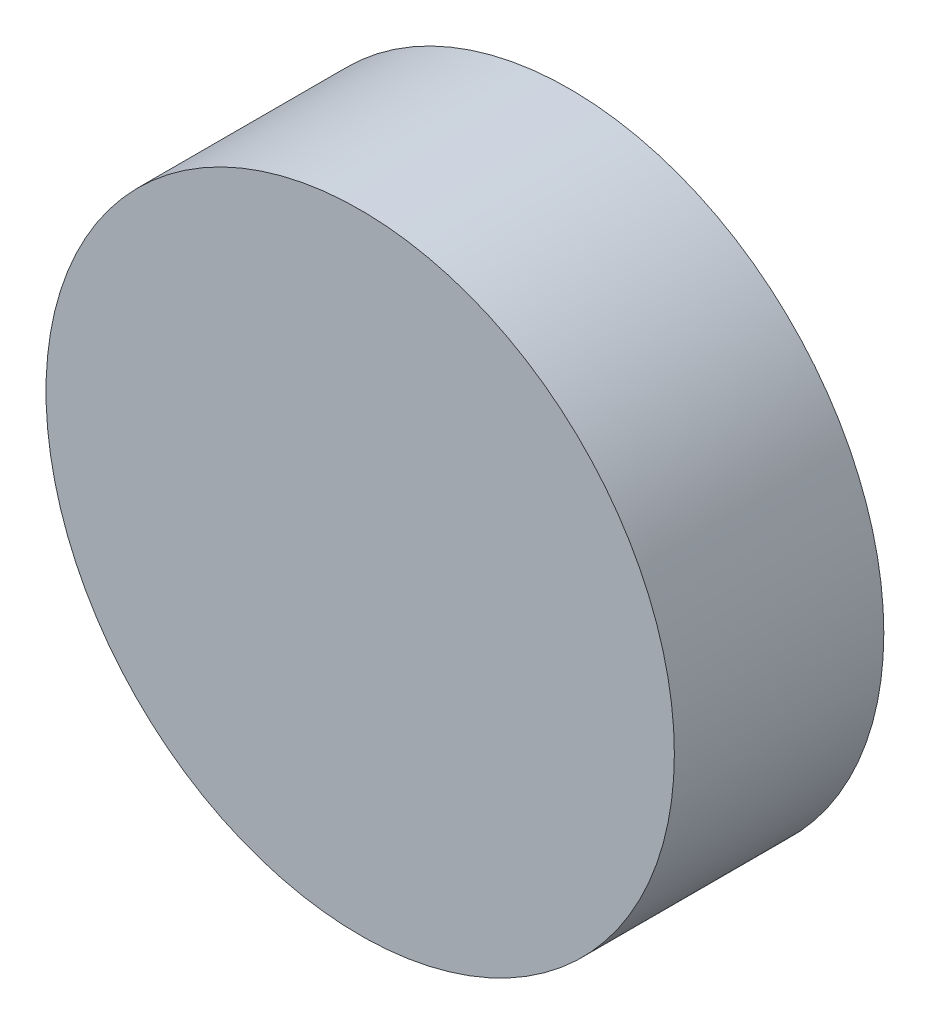
SolidWorks part; units mm, degrees
ref_plane "前视基准面" through (0, 0, 0) normal (0, 0, 1) x (1, 0, 0)
ref_plane "上视基准面" through (0, 0, 0) normal (0, 1, 0) x (1, 0, 0)
ref_plane "右视基准面" through (0, 0, 0) normal (1, 0, 0) x (0, 0, -1)
other "Configuration Table"
sketch "草图1" plane through (0, 0, 0) normal (0, 0, 1) x (1, 0, 0)
  circle A0 centre (0, 0) radius 1.65
  dimension "diameter" = 3.3
extrude "Disc" add sketch "草图1" along normal blind 1.1
